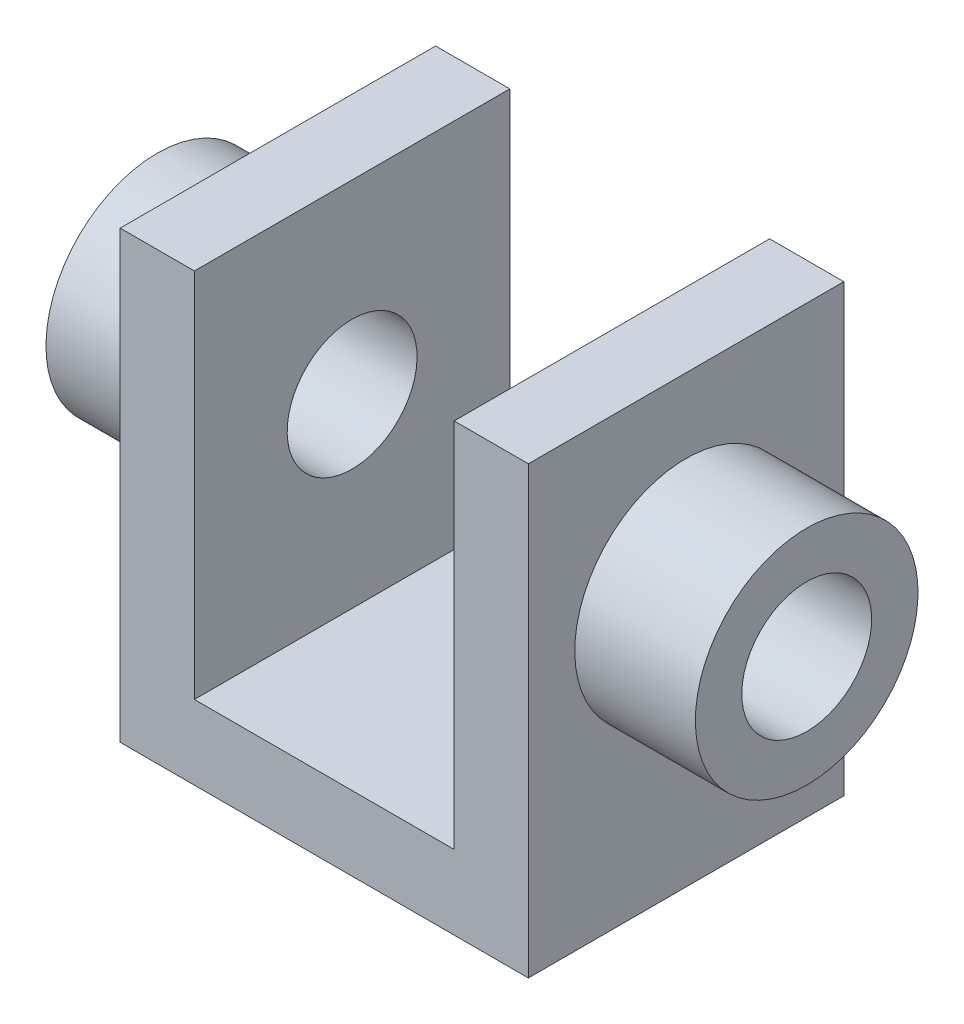
SolidWorks part; units mm, degrees
ref_plane "Front Plane" through (0, 0, 0) normal (0, 0, 1) x (1, 0, 0)
ref_plane "Top Plane" through (0, 0, 0) normal (0, 1, 0) x (1, 0, 0)
ref_plane "Right Plane" through (0, 0, 0) normal (1, 0, 0) x (0, 0, -1)
sketch "Sketch1" plane through (0, 0, 0) normal (0, 0, 1) x (1, 0, 0)
  line L0 (0, 0) -> (44, 0)
  line L1 (44, 0) -> (44, 48)
  line L2 (44, 48) -> (36, 48)
  line L3 (36, 48) -> (36, 8)
  line L4 (36, 8) -> (8, 8)
  line L5 (8, 8) -> (8, 48)
  line L6 (8, 48) -> (0, 48)
  line L7 (0, 48) -> (0, 0)
  dimension "D1" = 44
  dimension "D2" = 8
  dimension "D3" = 8
  dimension "D4" = 8
  dimension "D5" = 48
  dimension "D6" = 48
extrude "Boss-Extrude1" add sketch "Sketch1" against normal blind 34
sketch "Sketch2" plane through (0, 0, 0) normal (-1, 0, 0) x (0, 0, 1)
  line L0 (-34, 48) -> (-34, 0) construction
  line L4 (-34, 8) -> (0, 8) construction
  circle A0 centre (-17, 28) radius 7
  circle A1 centre (-17, 28) radius 12
  point P7 (-17, 29.1047)
  dimension "D1" = 14
  dimension "D2" = 24
  dimension "D4" = 17
  dimension "D3" = 20
extrude "Boss-Extrude3" add sketch "Sketch2" along normal blind 13
sketch "Sketch4" plane through (36, 0, 0) normal (-1, 0, 0) x (0, 0, 1)
  line L0 (-34, 8) -> (0, 8) construction
  line L1 (-34, 48) -> (-34, 8) construction
  circle A0 centre (-17, 28) radius 7
  circle A1 centre (-17, 28) radius 12
  point P7 (0, 0)
  dimension "D1" = 14
  dimension "D2" = 24
  dimension "D3" = 20
  dimension "D4" = 17
extrude "Boss-Extrude5" add sketch "Sketch4" against normal blind 21
sketch "Sketch9" plane through (44, 0, 0) normal (1, 0, 0) x (0, 0, -1)
  circle A0 centre (17, 28) radius 7
  point P5 (0, 0)
  point P10 (0, 0)
  dimension "D1" = 14
extrude "Cut-Extrude1" cut sketch "Sketch9" against normal blind 8
sketch "Sketch10" plane through (0, 0, 0) normal (-1, 0, 0) x (0, 0, 1)
  circle A0 centre (-17, 28) radius 7
  point P3 (0, 0)
  dimension "D1" = 14
extrude "Cut-Extrude2" cut sketch "Sketch10" against normal blind 8
